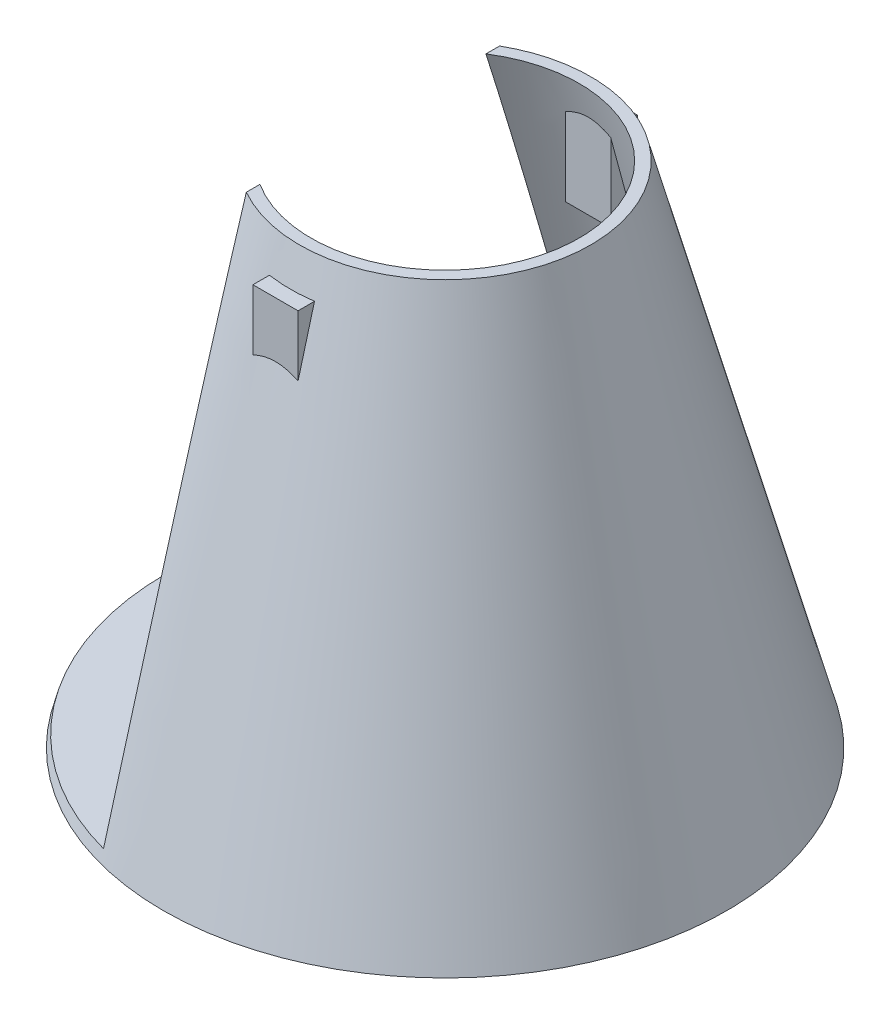
SolidWorks part; units mm, degrees
ref_plane "Ebene vorne" through (0, 0, 0) normal (0, 0, 1) x (1, 0, 0)
ref_plane "Ebene oben" through (0, 0, 0) normal (0, 1, 0) x (1, 0, 0)
ref_plane "Ebene rechts" through (0, 0, 0) normal (1, 0, 0) x (0, 0, -1)
sketch "Skizze2" plane through (0, 0, 0) normal (0, 0, 1) x (1, 0, 0)
  line L0 (0, 0) -> (75, 0)
  line L1 (55, 0) -> (-55, 0) construction
  line L2 (75, 0) -> (38.7653, 135.2296)
  line L3 (38.7653, 135.2296) -> (35.6595, 135.2296)
  line L4 (35.6595, 135.2296) -> (71.0903, 3)
  line L5 (71.0903, 3) -> (0, 3)
  line L6 (0, -55) -> (0, 55) construction
  line L7 (0, 3) -> (0, 0)
  dimension "D1" = 75
  dimension "D2" = 140
  dimension "D3" = 3
  dimension "D4" = 3
  dimension "D5" = 75
revolve "Rotation1" add sketch "Skizze2" angle 360 about L7
sketch "Skizze3" plane through (0, 0, 0) normal (0, 0, 1) x (1, 0, 0)
  line L4 (-38.7653, 135.2296) -> (-75, 0) construction
  line L5 (-74.1962, 3) -> (-19.1962, 3)
  line L7 (-74.1962, 3) -> (-38.7653, 135.2296)
  line L9 (-19.1962, 3) -> (-19.1962, 135.2296)
  line L10 (35.6595, 135.2296) -> (-35.6595, 135.2296) construction
  line L11 (-19.1962, 135.2296) -> (-38.7653, 135.2296)
  dimension "D1" = 132.2296
  dimension "D2" = 55
extrude "Schnitt-Linear austragen1" cut sketch "Skizze3" against normal through all both and the other way through all
sketch "Skizze4" plane through (0, 3, 0) normal (0, 1, 0) x (1, 0, 0)
  line L5 (0, 0) -> (0, 11.5) construction
  line L6 (3.5, -17) -> (3.5, -9)
  line L11 (10.5, 32) -> (-10.5, 32)
  line L12 (10.5, 32) -> (10.5, -9)
  line L14 (-4.5, -24.35) -> (4.5, -24.35) construction
  line L15 (0, -74.3763) -> (0, 74.3763) construction
  line L18 (10.5, -9) -> (3.5, -9)
  line L19 (-10.5, 32) -> (-10.5, -9)
  line L20 (10.5, 32) -> (-10.5, -9) construction
  line L21 (10.5, -9) -> (-10.5, 32) construction
  line L22 (-13.5, -17) -> (-3.5, -17)
  line L23 (-13.5, -17) -> (-13.5, 40)
  line L24 (-13.5, 40) -> (13.5, 40)
  line L25 (13.5, -17) -> (13.5, 40)
  line L26 (-13.5, -17) -> (13.5, 40) construction
  line L27 (-13.5, 40) -> (13.5, -17) construction
  line L28 (-3.5, -17) -> (-3.5, -9)
  line L29 (3.5, -17) -> (13.5, -17)
  line L30 (-3.5, -9) -> (-10.5, -9)
  point P0 (0, 0)
  point P6 (0, 0)
  point P17 (0, -24.35)
  dimension "D1" = 11.5
  dimension "D2" = 41
  dimension "D3" = 21
  dimension "D4" = 3
  dimension "D5" = 0
  dimension "D6" = 8
  dimension "D7" = 3.5
  dimension "D8" = 3.5
extrude "Aufsatz-Linear austragen1" add sketch "Skizze4" along normal blind 29
sketch "Skizze6" plane through (-13.5, 0, 0) normal (-1, 0, 0) x (0, 0, 1)
  line L0 (-40, 19.4565) -> (17, 19.4565) construction
  line L1 (-40, 32) -> (-40, 3) construction
  line L2 (17, 32) -> (17, 3) construction
  line L3 (-11.5, 19.4565) -> (-30, 32)
  line L4 (-40, 32) -> (17, 32) construction
  line L5 (-30, 32) -> (7, 32)
  line L6 (7, 32) -> (-11.5, 19.4565)
  dimension "D1" = 10
  dimension "D2" = 10
extrude "Schnitt-Linear austragen3" cut sketch "Skizze6" against normal blind 39
sketch "Skizze7" plane through (0, 0, 0) normal (0, 0, 1) x (1, 0, 0)
  line L0 (0, -74.3763) -> (0, 74.3763) construction
  line L2 (38.7653, 135.2296) -> (-19.1962, 135.2296) construction
  arc A0 (2.8527, 114.9512) -> (-2.8527, 114.9512) centre (0, 120.2296) ccw
  arc A1 (-2.8527, 114.9512) -> (2.8527, 114.9512) centre (0, 114.4296) ccw
  point P8 (0, 133.5577)
  point P10 (0, 111.5296)
  point P11 (0, 126.2296)
  dimension "D1" = 12
  dimension "D2" = 5.8
  dimension "D3" = 14.7
  dimension "D4" = 15
extrude "Schnitt-Linear austragen4" cut sketch "Skizze7" against normal through all both and the other way through all contours A0 A1
ref_plane "Ebene1" through (0, 0, -45.1157) normal (0, 0, 1) x (1, 0, 0)
sketch "Skizze8" plane through (0, 0, -45.1157) normal (0, 0, 1) x (1, 0, 0)
  line L0 (0, -74.3763) -> (0, 74.3763) construction
  line L1 (-6, 126.2296) -> (6, 126.2296)
  line L2 (-6, 126.2296) -> (-6, 103.7296)
  line L3 (-6, 103.7296) -> (6, 103.7296)
  line L4 (6, 126.2296) -> (6, 103.7296)
  arc A1 (2.8527, 114.9512) -> (-2.8527, 114.9512) centre (0, 120.2296) ccw construction
  point P6 (0, 126.2296)
  dimension "D1" = 6
  dimension "D2" = 6
  dimension "D3" = 22.5
  dimension "D4" = 0
extrude "Aufsatz-Linear austragen2" add sketch "Skizze8" along normal blind 7.05
ref_plane "Ebene2" through (0, 0, 45.1157) normal (0, 0, 1) x (1, 0, 0)
sketch "Skizze9" plane through (0, 0, 45.1157) normal (0, 0, 1) x (1, 0, 0)
  line L0 (0, 126.2296) -> (0, 103.7296) construction
  line L1 (-6, 126.2296) -> (6, 126.2296)
  line L2 (-6, 126.2296) -> (-6, 103.7296)
  line L3 (-6, 103.7296) -> (6, 103.7296)
  line L4 (6, 126.2296) -> (6, 103.7296)
  line L5 (0, -74.3763) -> (0, 74.3763) construction
  arc A0 (2.8527, 114.9512) -> (-2.8527, 114.9512) centre (0, 120.2296) ccw construction
  point P4 (0, 126.2296)
  dimension "D1" = 12
  dimension "D2" = 0
  dimension "D3" = 0
  dimension "D4" = 22.5
extrude "Aufsatz-Linear austragen3" add sketch "Skizze9" against normal blind 7.05
